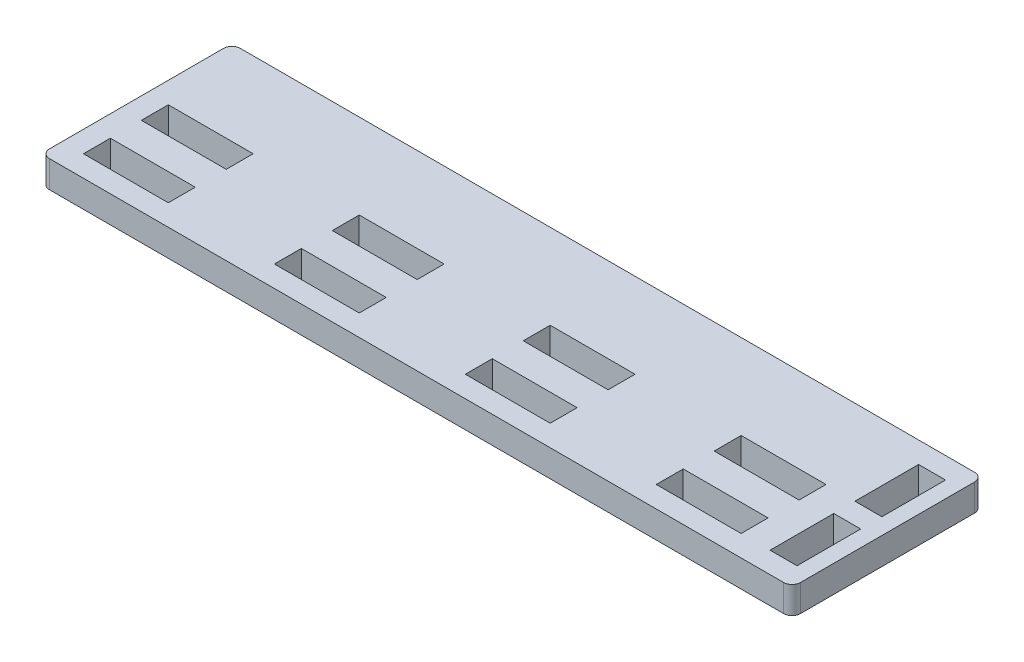
SolidWorks part; units mm, degrees
ref_plane "Front Plane" through (0, 0, 0) normal (0, 0, 1) x (1, 0, 0)
ref_plane "Top Plane" through (0, 0, 0) normal (0, 1, 0) x (1, 0, 0)
ref_plane "Right Plane" through (0, 0, 0) normal (1, 0, 0) x (0, 0, -1)
sketch "Sketch1" plane through (0, 0, 0) normal (0, 1, 0) x (1, 0, 0)
  line L0 (0, 0) -> (0, 20) construction
  line L1 (0, 0) -> (0, -25) construction
  line L2 (0, 0) -> (-170, 0) construction
  line L3 (-170, 0) -> (-170, 20)
  line L4 (-170, 20) -> (0, 20)
  line L6 (0, -25) -> (-170, -25)
  line L7 (-170, -25) -> (-170, 0)
  line L8 (0, 0) -> (7, 0) construction
  line L9 (0, -25) -> (7, -25)
  line L10 (7, -25) -> (7, 20)
  line L11 (7, 20) -> (0, 20)
  dimension "D1" = 20
  dimension "D2" = 25
  dimension "D3" = 170
  dimension "D4" = 7
extrude "Boss-Extrude1" add sketch "Sketch1" along normal blind 6.35
sketch "Sketch2" plane through (0, 6.35, 0) normal (0, 1, 0) x (1, 0, 0)
  line L0 (0, 0) -> (7, 0) construction
  line L1 (7, -25) -> (7, 20) construction
  line L2 (0, 0) -> (0, 20) construction
  line L3 (7, 20) -> (-170, 20) construction
  line L4 (0, 0) -> (-170, 0) construction
  line L5 (-170, 20) -> (-170, -25) construction
  line L6 (0, 0) -> (0, -25) construction
  line L7 (-170, -25) -> (7, -25) construction
  line L8 (-120, -13.65) -> (-100, -13.65)
  line L9 (-165, -13.65) -> (-145, -13.65)
  line L10 (-165, -13.65) -> (-165, -20)
  line L11 (-165, -20) -> (-145, -20)
  line L12 (-145, -13.65) -> (-145, -20)
  line L41 (-120, -13.65) -> (-120, -20)
  line L42 (-120, -20) -> (-100, -20)
  line L43 (-100, -13.65) -> (-100, -20)
  line L44 (-75, -13.65) -> (-55, -13.65)
  line L45 (-75, -13.65) -> (-75, -20)
  line L46 (-75, -20) -> (-55, -20)
  line L47 (-55, -13.65) -> (-55, -20)
  line L48 (-30, -13.65) -> (-10, -13.65)
  line L49 (-30, -13.65) -> (-30, -20)
  line L50 (-30, -20) -> (-10, -20)
  line L51 (-10, -13.65) -> (-10, -20)
  line L60 (-165, -13.65) -> (-120, -13.65) construction
  line L61 (-120, 0) -> (-120, -6.35)
  line L62 (-165, 0) -> (-145, 0)
  line L63 (-165, 0) -> (-165, -6.35)
  line L64 (-165, -6.35) -> (-145, -6.35)
  line L65 (-145, 0) -> (-145, -6.35)
  line L66 (-120, 0) -> (-100, 0)
  line L67 (-100, 0) -> (-100, -6.35)
  line L68 (-120, -6.35) -> (-100, -6.35)
  line L69 (-75, 0) -> (-75, -6.35)
  line L70 (-75, 0) -> (-55, 0)
  line L71 (-55, 0) -> (-55, -6.35)
  line L72 (-75, -6.35) -> (-55, -6.35)
  line L73 (-30, 0) -> (-30, -6.35)
  line L74 (-30, 0) -> (-10, 0)
  line L75 (-10, 0) -> (-10, -6.35)
  line L76 (-30, -6.35) -> (-10, -6.35)
  line L77 (-165, 0) -> (-120, 0) construction
  dimension "D1" = 4
  dimension "D2" = 45
  dimension "D3" = 20
  dimension "D4" = 6.35
  dimension "D5" = 5
  dimension "D6" = 5
  dimension "D7" = 20
  dimension "D8" = 6.35
  dimension "D9" = 5
  dimension "D11" = 45
  dimension "D10" = 4
extrude "Cut-Extrude1" cut sketch "Sketch2" against normal through all contours L63 L62 L65 L64 | L10 L9 L12 L11 | L61 L68 L67 L66 | L8 L43 L42 L41 | L69 L72 L71 L70 | L44 L47 L46 L45 | L48 L51 L50 L49 | L73 L76 L75 L74
sketch "Sketch4" plane through (0, 6.35, 0) normal (0, 1, 0) x (1, 0, 0)
  line L0 (0, 0) -> (7, 0) construction
  line L1 (7, -25) -> (7, 20) construction
  line L2 (0, 0) -> (0, -25) construction
  line L3 (-170, -25) -> (7, -25) construction
  line L4 (0, 0) -> (0, 20) construction
  line L5 (7, 20) -> (-170, 20) construction
  line L6 (0, 0) -> (-170, 0) construction
  line L7 (-170, 20) -> (-170, -25) construction
  line L9 (3.175, -20) -> (-3.175, -20)
  line L10 (3.175, -20) -> (3.175, -5)
  line L11 (3.175, -5) -> (-3.175, -5)
  line L12 (-3.175, -20) -> (-3.175, -5)
  line L13 (-3.175, 15) -> (3.175, 15)
  line L14 (-3.175, 15) -> (-3.175, 0)
  line L15 (-3.175, 0) -> (3.175, 0)
  line L16 (3.175, 15) -> (3.175, 0)
  point P18 (0, -20)
  point P23 (0, 0)
  dimension "D1" = 6.35
  dimension "D2" = 15
  dimension "D3" = 5
  dimension "D4" = 6.35
  dimension "D5" = 15
  dimension "D6" = 5
extrude "Cut-Extrude2" cut sketch "Sketch4" against normal through all
fillet "Fillet1" radius 2 4 edges at (7, 3.175, -20) (7, 3.175, 25) (-170, 3.175, 25) (-170, 3.175, -20)
